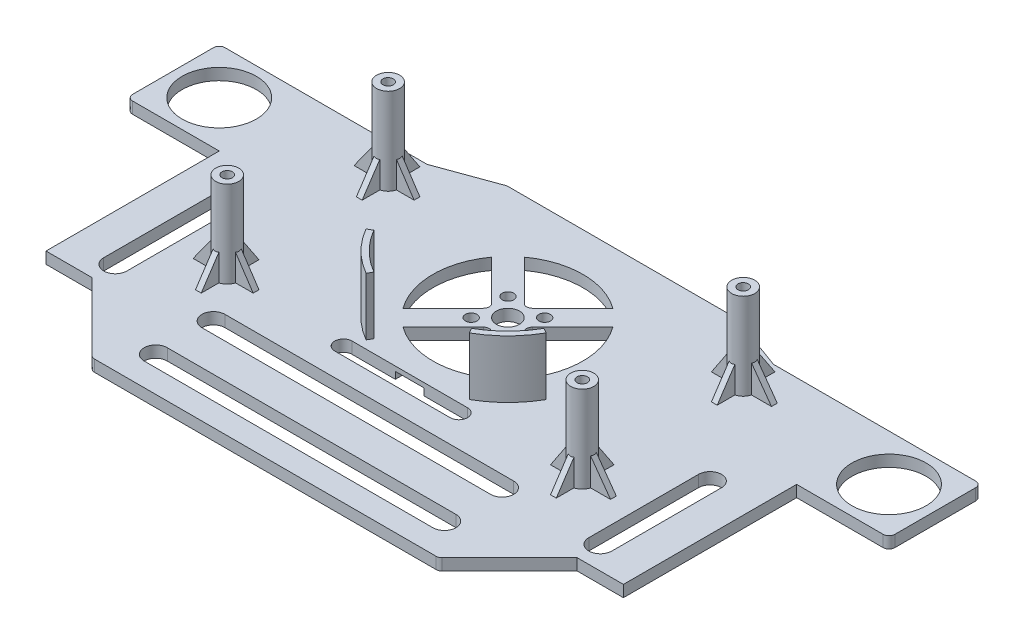
SolidWorks part; units mm, degrees
ref_plane "前视基准面" through (0, 0, 0) normal (0, 0, 1) x (1, 0, 0)
ref_plane "上视基准面" through (0, 0, 0) normal (0, 1, 0) x (1, 0, 0)
ref_plane "右视基准面" through (0, 0, 0) normal (1, 0, 0) x (0, 0, -1)
other "Configuration Table"
sketch "草图1" plane through (0, 0, 0) normal (0, 1, 0) x (1, 0, 0)
  line L0 (-50, 23) -> (50, 23)
  line L1 (50, 23) -> (50, -23)
  line L2 (50, -23) -> (32.2409, -23)
  line L3 (-50, -23) -> (-50, 23)
  line L5 (0, 23) -> (0, -23) construction
  line L6 (3.182, 10.182) -> (-3.182, 3.818) construction
  line L7 (7.6687, 17.4972) -> (-10.4972, -0.6687) construction
  line L8 (10.4972, 14.6687) -> (-7.6687, -3.4972) construction
  line L9 (10.4972, -0.6687) -> (-7.6687, 17.4972) construction
  line L10 (7.6687, -3.4972) -> (-10.4972, 14.6687) construction
  line L11 (-7.6687, -3.4972) -> (10.4972, 14.6687) construction
  line L12 (-10.4972, -0.6687) -> (7.6687, 17.4972) construction
  line L13 (-10.4972, 14.6687) -> (7.6687, -3.4972) construction
  line L14 (-7.6687, 17.4972) -> (10.4972, -0.6687) construction
  line L15 (10.4972, -0.6687) -> (3.5355, 6.2929)
  line L16 (3.5355, 7.7071) -> (10.4972, 14.6687)
  line L17 (7.6687, 17.4972) -> (0.7071, 10.5355)
  line L18 (-0.7071, 10.5355) -> (-7.6687, 17.4972)
  line L19 (-10.4972, 14.6687) -> (-3.5355, 7.7071)
  line L20 (-3.5355, 6.2929) -> (-10.4972, -0.6687)
  line L21 (-7.6687, -3.4972) -> (-0.7071, 3.4645)
  line L22 (0.7071, 3.4645) -> (7.6687, -3.4972)
  line L23 (-30, 23) -> (-19.848, 26.695)
  line L24 (-19.848, 26.695) -> (0, 26.695)
  line L25 (30, 23) -> (19.848, 26.695)
  line L26 (19.848, 26.695) -> (0, 26.695)
  line L27 (-50, 23) -> (-66, 23)
  line L28 (-66, 23) -> (-66, 7)
  line L29 (-66, 7) -> (-50, 7)
  line L30 (-50, 7) -> (-50, 23)
  line L39 (50, 7) -> (50, 23)
  line L40 (66, 7) -> (50, 7)
  line L41 (66, 23) -> (66, 7)
  line L42 (50, 23) -> (66, 23)
  line L43 (-42, -23) -> (-30, -35)
  line L44 (-30, -35) -> (30, -35)
  line L45 (42, -23) -> (30, -35)
  line L46 (-42, -23) -> (-32.2409, -23)
  line L47 (-46, 23) -> (-46, -23) construction
  line L48 (-50, 0) -> (50, 0) construction
  line L49 (-10, -11.5) -> (10, -11.5) construction
  line L50 (-10, -10) -> (10, -10)
  line L51 (-25, -19) -> (25, -19) construction
  line L52 (-25, -17) -> (25, -17)
  line L53 (-25, -21) -> (25, -21)
  line L54 (-25, -29) -> (25, -29) construction
  line L55 (-25, -27) -> (25, -27)
  line L56 (-25, -31) -> (25, -31)
  line L57 (-10, -13) -> (10, -13)
  line L58 (-42, -19) -> (-42, 0) construction
  line L59 (-29.2521, -23) -> (29.2521, -23)
  line L60 (-32.2409, -23) -> (-50, -23)
  line L61 (32.2409, -23) -> (42, -23)
  line L62 (29.2521, -23) -> (-29.2521, -23)
  line L63 (-44, -19) -> (-44, 0)
  line L64 (-40, -19) -> (-40, 0)
  line L65 (42, -19) -> (42, 0) construction
  line L66 (44, -19) -> (44, 0)
  line L67 (40, -19) -> (40, 0)
  circle A0 centre (0, 7) radius 2
  circle A1 centre (3.182, 10.182) radius 1
  circle A2 centre (3.182, 3.818) radius 1
  circle A3 centre (-3.182, 3.818) radius 1
  circle A4 centre (-3.182, 10.182) radius 1
  circle A5 centre (0, 7) radius 13
  arc A10 (-0.7071, 3.4645) -> (0.7071, 3.4645) centre (0, 2.7574) cw
  arc A11 (-3.5355, 7.7071) -> (-3.5355, 6.2929) centre (-4.2426, 7) cw
  arc A12 (0.7071, 10.5355) -> (-0.7071, 10.5355) centre (0, 11.2426) cw
  arc A13 (3.5355, 6.2929) -> (3.5355, 7.7071) centre (4.2426, 7) cw
  circle A15 centre (-58, 15) radius 6.425
  circle A16 centre (58, 15) radius 6.425
  circle A27 centre (0, 7) radius 15
  arc A29 (-25, -17) -> (-25, -21) centre (-25, -19) ccw
  arc A30 (25, -21) -> (25, -17) centre (25, -19) ccw
  arc A31 (-25, -27) -> (-25, -31) centre (-25, -29) ccw
  arc A32 (25, -31) -> (25, -27) centre (25, -29) ccw
  arc A33 (-10, -10) -> (-10, -13) centre (-10, -11.5) ccw
  arc A34 (10, -13) -> (10, -10) centre (10, -11.5) ccw
  arc A35 (-44, -19) -> (-40, -19) centre (-42, -19) ccw
  arc A36 (-40, 0) -> (-44, 0) centre (-42, 0) ccw
  arc A37 (44, -19) -> (40, -19) centre (42, -19) cw
  arc A38 (40, 0) -> (44, 0) centre (42, 0) cw
  point P5 (50, 0)
  point P6 (0, 23)
  point P25 (-42, -9.5)
  point P42 (0, 4.1716)
  point P45 (-2.8284, 7)
  point P48 (0, 9.8284)
  point P51 (2.8284, 7)
  point P64 (-58, 23)
  point P66 (-66, 15)
  point P67 (42, -9.5)
  point P84 (0, -35)
  point P111 (0, -11.5)
  point P116 (0, -19)
  point P122 (0, -29)
  dimension "D3" = 4
  dimension "D4" = 2
  dimension "D8" = 26
  dimension "D9" = 2
  dimension "D13" = 1
  dimension "D18" = 16
  dimension "D19" = 16
  dimension "D20" = 12.85
  dimension "D27" = 4
  dimension "D35" = 30
  dimension "D36" = 1.5
  dimension "D1" = 100
  dimension "D2" = 46
  dimension "D6" = 9
  dimension "D7" = 45
  dimension "D14" = 16
  dimension "D15" = 20
  dimension "D16" = 20
  dimension "D17" = 3.695
  dimension "D23" = 8
  dimension "D24" = 45
  dimension "D25" = 12
  dimension "D37" = 10
  dimension "D38" = 10
  dimension "D39" = 6
  dimension "D40" = 2
  dimension "D41" = 2
  dimension "D42" = 25
  dimension "D43" = 7.5
  dimension "D10" = 19
  dimension "D5" = 4
  dimension "D12" = 4
extrude "凸台-拉伸1" add sketch "草图1" along normal blind 2
sketch "草图2" plane through (0, 2, 0) normal (0, 1, 0) x (1, 0, 0)
  text T0 "M3" font "@Microsoft YaHei UI" height 2
  text T1 "M2" font "@Microsoft YaHei UI" height 2
  text T2 "M3" font "@Microsoft YaHei UI" height 2
sketch "草图3" plane through (0, 2, 0) normal (0, 1, 0) x (1, 0, 0)
  line L0 (-15.5999, -1.9801) -> (-14.7333, -1.4812)
  line L1 (19.848, 26.695) -> (-19.848, 26.695) construction
  line L2 (30, 23) -> (66, 23) construction
  line L3 (-8.4501, -7.7511) -> (-8.9472, -8.6188)
  line L4 (0, 26.695) -> (0, -8.7316) construction
  line L5 (8.4501, -7.7511) -> (8.9472, -8.6188)
  line L6 (15.5999, -1.9801) -> (14.7333, -1.4812)
  circle A0 centre (-30.7465, -10.87) radius 0.9
  circle A1 centre (-30.7465, -10.87) radius 2
  circle A2 centre (-30.7465, 17) radius 2
  circle A3 centre (-30.7465, 17) radius 0.9
  circle A10 centre (30.7465, -10.87) radius 2
  circle A11 centre (30.7465, 17) radius 2
  circle A14 centre (30.7465, 17) radius 0.9
  circle A15 centre (30.7465, -10.87) radius 0.9
  arc A20 (-12.7279, -5.7279) -> (-15.5999, -1.9801) centre (0, 7) cw
  arc A23 (-12.7279, -5.7279) -> (-8.9472, -8.6188) centre (0, 7) ccw
  arc A24 (-12.0208, -5.0208) -> (-8.4501, -7.7511) centre (0, 7) ccw
  arc A25 (-12.0208, -5.0208) -> (-14.7333, -1.4812) centre (0, 7) cw
  arc A26 (12.0208, -5.0208) -> (14.7333, -1.4812) centre (0, 7) ccw
  arc A27 (12.0208, -5.0208) -> (8.4501, -7.7511) centre (0, 7) cw
  arc A28 (12.7279, -5.7279) -> (8.9472, -8.6188) centre (0, 7) cw
  arc A29 (12.7279, -5.7279) -> (15.5999, -1.9801) centre (0, 7) ccw
  point P0 (0, 0)
  dimension "D3" = 1.8
  dimension "D4" = 4
  dimension "D9" = 30.7465
  dimension "D8" = 32.4229
  dimension "D1" = 27.87
  dimension "D2" = 6
  dimension "D5" = 1
  dimension "D6" = 12.7279
extrude "凸台-拉伸6" add sketch "草图3" along normal blind 15
sketch "草图5" plane through (0, 2, 0) normal (0, 1, 0) x (1, 0, 0)
  circle A8 centre (30.7465, 17) radius 0.9 construction
  circle A9 centre (30.7465, -10.87) radius 0.9 construction
  circle A10 centre (-30.7465, -10.87) radius 0.9 construction
  circle A11 centre (-30.7465, 17) radius 0.9 construction
  circle A12 centre (30.7465, 17) radius 0.9
  circle A13 centre (30.7465, -10.87) radius 0.9
  circle A14 centre (-30.7465, -10.87) radius 0.9
  circle A15 centre (-30.7465, 17) radius 0.9
extrude "凸台-拉伸7" add sketch "草图5" along normal blind 6
sketch "草图7" plane through (0, 0, 0) normal (0, -1, 0) x (1, 0, 0)
  line L1 (-2.5, 10) -> (2.5, 10)
  line L2 (-2.5, 10) -> (-2.5, 5.7574)
  line L3 (-2.5, 5.7574) -> (2.5, 5.7574)
  line L4 (2.5, 10) -> (2.5, 5.7574)
  line L5 (-2.5, 10) -> (2.5, 5.7574) construction
  line L6 (-2.5, 5.7574) -> (2.5, 10) construction
  line L7 (-10, 10) -> (10, 10) construction
  line L8 (0, -7) -> (0, 13) construction
  line L9 (-10, 13) -> (10, 13) construction
  arc A2 (7.6687, 3.4972) -> (-7.6687, 3.4972) centre (0, -7) ccw construction
  point P0 (0, 7.8787)
  dimension "D1" = 5
extrude "切除-拉伸2" cut sketch "草图7" against normal blind 1.2
fillet "圆角1" radius 1 8 edges at (-19.848, 1, -26.695) (19.848, 1, -26.695) (66, 1, -23) (30, 1, 35) (-30, 1, 35) (-66, 1, -23) (66, 1, -7) (-66, 1, -7)
ref_plane "基准面1" through (0, 0, -17) normal (0, 0, 1) x (1, 0, 0)
ref_plane "基准面2" through (-30.7465, 0, 0) normal (-1, 0, 0) x (0, 0, 1)
sketch "草图15" plane through (0, 2, 0) normal (0, 1, 0) x (1, 0, 0)
  line L0 (0, 26.695) -> (0, -35) construction
  line L1 (19.6717, 26.695) -> (-19.6717, 26.695) construction
  line L2 (-29.5858, -35) -> (29.5858, -35) construction
sketch "草图8" plane through (0, 0, -17) normal (0, 0, 1) x (1, 0, 0)
  line L0 (-32.7465, 9.5) -> (-28.7465, 9.5) construction
  line L1 (-32.7465, 17) -> (-32.7465, 2) construction
  line L2 (-28.7465, 2) -> (-28.7465, 17) construction
  line L3 (-30.7465, 9.5) -> (-36.1464, 2)
  line L4 (-42, 2) -> (-30.2929, 2) construction
sketch "草图9" plane through (0, 2, 0) normal (0, 1, 0) x (1, 0, 0)
  line L0 (-32.7465, 17) -> (-28.7465, 17) construction
  line L1 (-30.7465, 17) -> (-30.7465, -10.87) construction
  line L2 (-30.7465, 3.065) -> (35.839, 3.065) construction
  point P0 (-30.7465, 17)
  point P1 (-25.7465, 17)
  point P10 (-30.7465, 12)
  point P11 (-35.7465, 17)
  point P12 (-30.7465, 22)
  point P13 (-30.7465, 17)
  dimension "D1" = 2
  dimension "D2" = 4
ref_plane "基准面3" through (0, 0, -3.065) normal (0, 0, 1) x (1, 0, 0)
ref_plane "基准面4" through (0, 0, 0) normal (-1, 0, 0) x (0, 0, 1)
rib "筋1" sketch "草图8" sketch "草图8" thickness 1 extrusion direction parallel to sketch draft on no parameters "D1"=1
sketch "草图10" plane through (0, 0, -17) normal (0, 0, 1) x (1, 0, 0)
  line L0 (-28.7465, 9.5) -> (-32.7465, 9.5) construction
  line L1 (-28.7465, 2) -> (-28.7465, 17) construction
  line L2 (-32.7465, 17) -> (-32.7465, 2) construction
  line L3 (-30.7465, 9.5) -> (-25.7465, 2)
rib "筋2" sketch "草图10" sketch "草图10" thickness 1 extrusion direction parallel to sketch draft on no parameters "D1"=1
sketch "草图11" plane through (-30.7465, 0, 0) normal (-1, 0, 0) x (0, 0, 1)
  line L0 (-19, 9.5) -> (-15, 9.5) construction
  line L1 (-19, 17) -> (-19, 2) construction
  line L2 (-15, 2) -> (-15, 17) construction
  line L3 (-17, 9.5) -> (-22, 2)
rib "筋3" sketch "草图11" sketch "草图11" thickness 1 extrusion direction parallel to sketch draft on no parameters "D1"=1
sketch "草图12" plane through (-30.7465, 0, 0) normal (-1, 0, 0) x (0, 0, 1)
  line L0 (-15, 9.5) -> (-19, 9.5) construction
  line L1 (-15, 2) -> (-15, 17) construction
  line L2 (-19, 17) -> (-19, 6.5) construction
  line L3 (-17, 9.5) -> (-12, 2)
rib "筋4" sketch "草图12" sketch "草图12" thickness 1 extrusion direction parallel to sketch draft on no parameters "D1"=1
mirror "镜向1" about plane through (0, 0, 0) normal (-1, 0, 0) of "筋4", "筋3", "筋2", "筋1" second plane through (0, 0, -3.065) second plane normal (0, 0, 1)
sketch "草图16" plane through (0, 17, 0) normal (0, 1, 0) x (1, 0, 0)
  line L0 (8.4501, -7.7511) -> (8.9472, -8.6188) construction
  line L1 (15.5999, -1.9801) -> (14.7333, -1.4812) construction
  line L2 (-8.9472, -8.6188) -> (-8.4501, -7.7511) construction
  line L3 (-14.7333, -1.4812) -> (-15.5999, -1.9801) construction
  line L4 (8.4501, -7.7511) -> (8.9472, -8.6188)
  line L5 (15.5999, -1.9801) -> (14.7333, -1.4812)
  line L6 (-8.9472, -8.6188) -> (-8.4501, -7.7511)
  line L7 (-14.7333, -1.4812) -> (-15.5999, -1.9801)
  arc A0 (8.4501, -7.7511) -> (14.7333, -1.4812) centre (0, 7) ccw construction
  arc A1 (8.9472, -8.6188) -> (15.5999, -1.9801) centre (0, 7) ccw construction
  arc A2 (-15.5999, -1.9801) -> (-8.9472, -8.6188) centre (0, 7) ccw construction
  arc A3 (-14.7333, -1.4812) -> (-8.4501, -7.7511) centre (0, 7) ccw construction
  arc A4 (8.4501, -7.7511) -> (14.7333, -1.4812) centre (0, 7) ccw
  arc A5 (8.9472, -8.6188) -> (15.5999, -1.9801) centre (0, 7) ccw
  arc A6 (-15.5999, -1.9801) -> (-8.9472, -8.6188) centre (0, 7) ccw
  arc A7 (-14.7333, -1.4812) -> (-8.4501, -7.7511) centre (0, 7) ccw
extrude "切除-拉伸3" cut sketch "草图16" against normal blind 5
